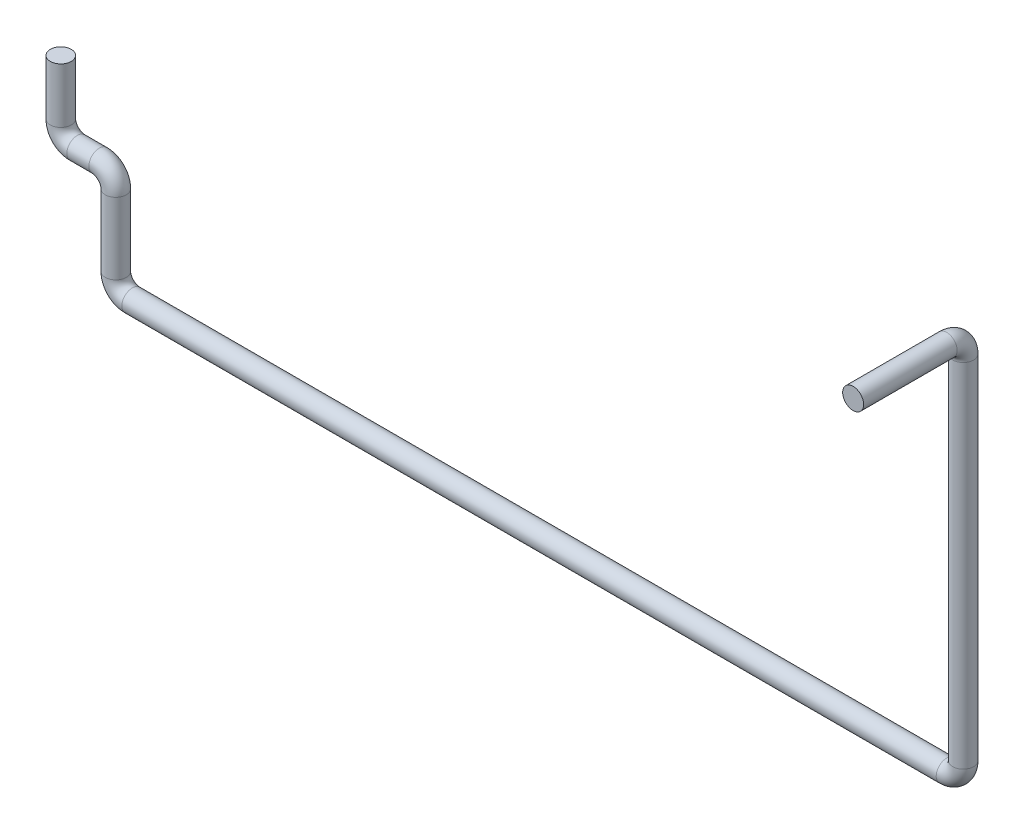
SolidWorks part; units mm, degrees
ref_plane "Alzado" through (0, 0, 0) normal (0, 0, 1) x (1, 0, 0)
ref_plane "Planta" through (0, 0, 0) normal (0, 1, 0) x (1, 0, 0)
ref_plane "Vista lateral" through (0, 0, 0) normal (1, 0, 0) x (0, 0, -1)
sketch "Croquis1" plane through (0, 0, 0) normal (0, 1, 0) x (1, 0, 0)
  circle A0 centre (0, 0) radius 9.525
  dimension "D1" = 19.05
extrude "Saliente-Extruir1" add sketch "Croquis1" against normal blind 10
sketch3d "Croquis3D1"
  line L0 (0, -10, 0) -> (0, -50, 0)
  line L1 (0, -10, 0) -> (0, 0, 0) construction
  line L2 (15, -65, 0) -> (35, -65, 0)
  line L3 (50, -80, 0) -> (50, -145, 0)
  line L4 (65, -160, 0) -> (805, -160, 0)
  line L5 (820, -145, 0) -> (820, 175, 0)
  line L6 (820, 190, 15) -> (820, 190, 100)
  arc A0 (35, -65, 0) -> (50, -80, 0) centre (35, -80, 0) ccw
  arc A1 (0, -50, 0) -> (15, -65, 0) centre (15, -50, 0) ccw
  arc A2 (50, -145, 0) -> (65, -160, 0) centre (65, -145, 0) ccw
  arc A3 (820, 175, 0) -> (820, 190, 15) centre (820, 175, 15) ccw
  arc A4 (805, -160, 0) -> (820, -145, 0) centre (805, -145, 0) ccw
  point P12 (50, -65, 0)
  point P13 (35, -80, -15)
  point P16 (0, -65, 0)
  point P17 (15, -50, 15)
  point P18 (50, -160, 0)
  point P20 (50, -150, -185)
  point P21 (65, -145, 15)
  point P24 (50, -150, 0)
  point P25 (820, 190, 0)
  point P26 (835, 175, 15)
  point P28 (730, -150, -185)
  point P30 (820, -160, 0)
  point P31 (805, -145, 15)
  point P32 (730, 720, -185)
  dimension "D8" = 15
  dimension "D9" = 770
  dimension "D10" = 350
  dimension "D12" = 15
  dimension "D13" = 15
  dimension "D1" = 55
  dimension "D2" = 50
  dimension "D3" = 85
  dimension "D4" = 185
  dimension "D5" = 680
  dimension "D6" = 870
  dimension "D7" = 95
  dimension "D11" = 100
sketch "Croquis2" plane through (0, -10, 0) normal (0, -1, 0) x (1, 0, 0)
  circle A0 centre (0, 0) radius 9.525
sweep "Barrer1" add profiles "Croquis2" path "Croquis3D1"
